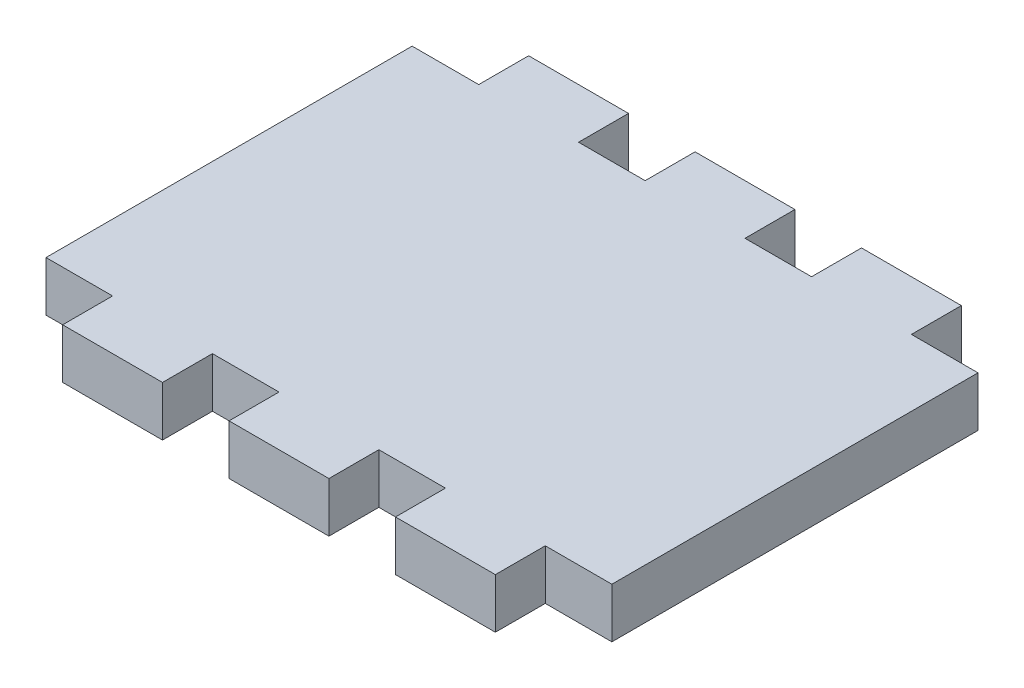
SolidWorks part; units mm, degrees
ref_plane "Front Plane" through (0, 0, 0) normal (0, 0, 1) x (1, 0, 0)
ref_plane "Top Plane" through (0, 0, 0) normal (0, 1, 0) x (1, 0, 0)
ref_plane "Right Plane" through (0, 0, 0) normal (1, 0, 0) x (0, 0, -1)
sketch "Sketch1" plane through (0, 0, 0) normal (0, 1, 0) x (1, 0, 0)
  line L1 (-17, -14) -> (17, -14)
  line L2 (-17, -14) -> (-17, 14)
  line L3 (-17, 14) -> (17, 14)
  line L4 (17, -14) -> (17, 14)
  line L5 (-17, -14) -> (17, 14) construction
  line L6 (-17, 14) -> (17, -14) construction
  point P0 (0, 0)
  dimension "D1" = 34
  dimension "D2" = 28
extrude "Boss-Extrude1" add sketch "Sketch1" along normal blind 3
sketch "Sketch2" plane through (0, 3, 0) normal (0, 1, 0) x (1, 0, 0)
  line L1 (-17, 14) -> (-13, 14)
  line L2 (-17, 14) -> (-17, 11)
  line L3 (-17, 11) -> (-13, 11)
  line L4 (-13, 14) -> (-13, 11)
  dimension "D1" = 4
  dimension "D2" = 3
extrude "Cut-Extrude1" cut sketch "Sketch2" against normal blind 3
pattern_linear "LPattern1" count 4 spacing 10 along (1, 0, 0) count 2 spacing 25 along (0, 0, 1) of "Cut-Extrude1"
